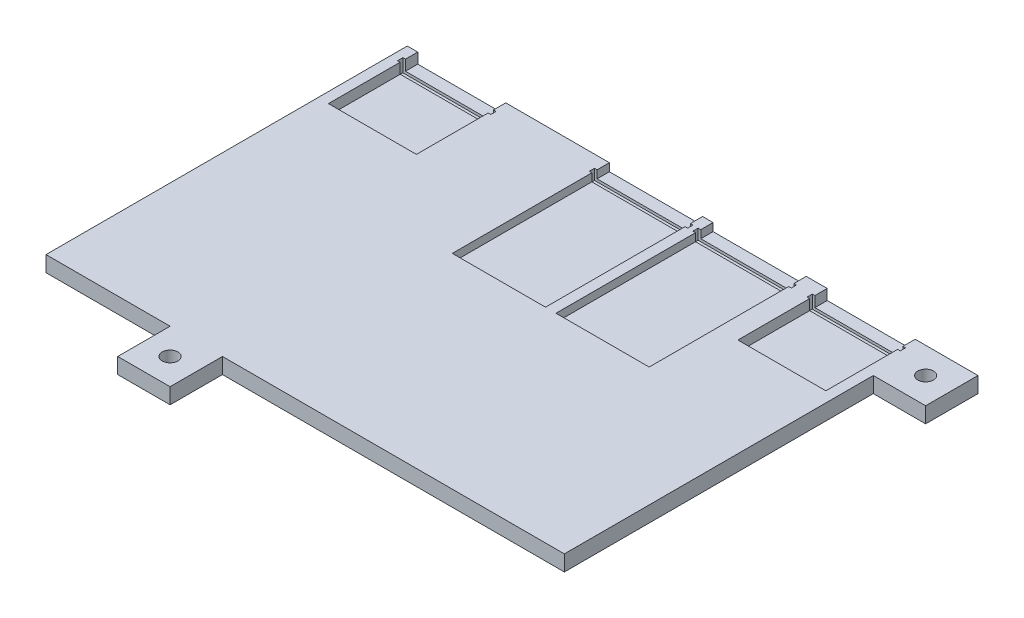
SolidWorks part; units mm, degrees
ref_plane "Front Plane" through (0, 0, 0) normal (0, 0, 1) x (1, 0, 0)
ref_plane "Top Plane" through (0, 0, 0) normal (0, 1, 0) x (1, 0, 0)
ref_plane "Right Plane" through (0, 0, 0) normal (1, 0, 0) x (0, 0, -1)
sketch "Sketch1" plane through (0, 0, 0) normal (0, 1, 0) x (1, 0, 0)
  line L1 (-49.5, 34.5) -> (49.5, 34.5)
  line L2 (-49.5, 34.5) -> (-49.5, -34.5)
  line L3 (-49.5, -34.5) -> (49.5, -34.5)
  line L4 (49.5, 34.5) -> (49.5, -34.5)
  line L5 (-49.5, 34.5) -> (49.5, -34.5) construction
  line L6 (-49.5, -34.5) -> (49.5, 34.5) construction
  point P4 (0, 0)
  point P5 (0, 0)
  dimension "D1" = 99
  dimension "D2" = 69
extrude "Boss-Extrude1" add sketch "Sketch1" along normal blind 3
sketch "Sketch2" plane through (0, 3, 0) normal (0, 1, 0) x (1, 0, 0)
  line L0 (-30.7, 32.1497) -> (-47.5, 32.1497) construction
  line L1 (-47.5, 32.1497) -> (-47.5, 34.5) construction
  line L2 (-47.5, 34.5) -> (-30.7, 34.5) construction
  line L3 (-30.7, 34.5) -> (-30.7, 32.1497) construction
  line L4 (-47.5, 31.1497) -> (-30.7, 31.1497) construction
  line L5 (-30.7, 31.1497) -> (-30.7, 17.4435) construction
  line L6 (-30.7, 17.4435) -> (-47.5, 17.4435) construction
  line L7 (-47.5, 17.4435) -> (-47.5, 31.1497) construction
  line L8 (6.9, 32.1497) -> (-10.9, 32.1497) construction
  line L9 (-10.9, 32.1497) -> (-10.9, 34.5) construction
  line L10 (-10.9, 34.5) -> (6.9, 34.5) construction
  line L11 (6.9, 34.5) -> (6.9, 32.1497) construction
  line L12 (-10.9, 31.1497) -> (6.9, 31.1497) construction
  line L13 (6.9, 31.1497) -> (6.9, 17.4435) construction
  line L14 (6.9, 17.4435) -> (-10.9, 17.4435) construction
  line L15 (-10.9, 17.4435) -> (-10.9, 31.1497) construction
  line L16 (8.9, 31.1497) -> (26.7, 31.1497) construction
  line L17 (26.7, 31.1497) -> (26.7, 17.4435) construction
  line L18 (26.7, 17.4435) -> (8.9, 17.4435) construction
  line L19 (8.9, 17.4435) -> (8.9, 31.1497) construction
  line L20 (26.7, 32.1497) -> (8.9, 32.1497) construction
  line L21 (8.9, 32.1497) -> (8.9, 34.5) construction
  line L22 (8.9, 34.5) -> (26.7, 34.5) construction
  line L23 (26.7, 34.5) -> (26.7, 32.1497) construction
  line L24 (47.5, 32.1497) -> (30.7, 32.1497) construction
  line L25 (30.7, 32.1497) -> (30.7, 34.5) construction
  line L26 (30.7, 34.5) -> (47.5, 34.5) construction
  line L27 (47.5, 34.5) -> (47.5, 32.1497) construction
  line L28 (30.7, 31.1497) -> (47.5, 31.1497) construction
  line L29 (47.5, 31.1497) -> (47.5, 17.4435) construction
  line L30 (47.5, 17.4435) -> (30.7, 17.4435) construction
  line L31 (30.7, 17.4435) -> (30.7, 31.1497) construction
  line L32 (-30.7, 32.1497) -> (-47.5, 32.1497)
  line L33 (-47.5, 32.1497) -> (-47.5, 34.5)
  line L34 (-47.5, 34.5) -> (-30.7, 34.5)
  line L35 (-30.7, 34.5) -> (-30.7, 32.1497)
  line L36 (-47.5, 31.1497) -> (-30.7, 31.1497)
  line L37 (-30.7, 31.1497) -> (-30.7, 17.4435)
  line L38 (-30.7, 17.4435) -> (-47.5, 17.4435)
  line L39 (-47.5, 17.4435) -> (-47.5, 31.1497)
  line L40 (6.9, 32.1497) -> (-10.9, 32.1497)
  line L41 (-10.9, 32.1497) -> (-10.9, 34.5)
  line L42 (-10.9, 34.5) -> (6.9, 34.5)
  line L43 (6.9, 34.5) -> (6.9, 32.1497)
  line L44 (-10.9, 31.1497) -> (6.9, 31.1497)
  line L45 (6.9, 31.1497) -> (6.9, 17.4435)
  line L46 (6.9, 17.4435) -> (-10.9, 17.4435)
  line L47 (-10.9, 17.4435) -> (-10.9, 31.1497)
  line L48 (8.9, 31.1497) -> (26.7, 31.1497)
  line L49 (26.7, 31.1497) -> (26.7, 17.4435)
  line L50 (26.7, 17.4435) -> (8.9, 17.4435)
  line L51 (8.9, 17.4435) -> (8.9, 31.1497)
  line L52 (26.7, 32.1497) -> (8.9, 32.1497)
  line L53 (8.9, 32.1497) -> (8.9, 34.5)
  line L54 (8.9, 34.5) -> (26.7, 34.5)
  line L55 (26.7, 34.5) -> (26.7, 32.1497)
  line L56 (47.5, 32.1497) -> (30.7, 32.1497)
  line L57 (30.7, 32.1497) -> (30.7, 34.5)
  line L58 (30.7, 34.5) -> (47.5, 34.5)
  line L59 (47.5, 34.5) -> (47.5, 32.1497)
  line L60 (30.7, 31.1497) -> (47.5, 31.1497)
  line L61 (47.5, 31.1497) -> (47.5, 17.4435)
  line L62 (47.5, 17.4435) -> (30.7, 17.4435)
  line L63 (30.7, 17.4435) -> (30.7, 31.1497)
sketch "Sketch4" plane through (0, 3, 0) normal (0, 1, 0) x (1, 0, 0)
  line L0 (47.5, 31.1497) -> (47.5, 17.4435) construction
  line L1 (47.5, 17.4435) -> (30.7, 17.4435) construction
  line L2 (30.7, 17.4435) -> (30.7, 31.1497) construction
  line L3 (-47.5, 17.4435) -> (-47.5, 31.1497) construction
  line L4 (-30.7, 31.1497) -> (-30.7, 17.4435) construction
  line L5 (-30.7, 17.4435) -> (-47.5, 17.4435) construction
  line L6 (47.5, 31.1497) -> (47.5, 17.4435)
  line L7 (47.5, 17.4435) -> (30.7, 17.4435)
  line L8 (30.7, 17.4435) -> (30.7, 31.1497)
  line L9 (-47.5, 17.4435) -> (-47.5, 31.1497)
  line L10 (-30.7, 31.1497) -> (-30.7, 17.4435)
  line L11 (-30.7, 17.4435) -> (-47.5, 17.4435)
  line L12 (-47.5, 31.1497) -> (-47.5, 34.5)
  line L13 (49.5, 34.5) -> (-49.5, 34.5) construction
  line L14 (-47.5, 34.5) -> (-30.7, 34.5)
  line L15 (-30.7, 34.5) -> (-30.7, 31.1497)
  line L16 (30.7, 31.1497) -> (30.7, 34.5)
  line L17 (30.7, 34.5) -> (47.5, 34.5)
  line L18 (47.5, 34.5) -> (47.5, 31.1497)
extrude "Cut-Extrude1" cut sketch "Sketch4" against normal blind 2
sketch "Sketch6" plane through (0, 1, 0) normal (0, 1, 0) x (1, 0, 0)
  line L1 (-47.5, 31.1497) -> (-48, 31.1497)
  line L2 (-47.5, 31.1497) -> (-47.5, 32.1497)
  line L3 (-47.5, 32.1497) -> (-48, 32.1497)
  line L4 (-48, 31.1497) -> (-48, 32.1497)
  line L5 (-47.5, 31.1497) -> (-48, 32.1497) construction
  line L6 (-47.5, 32.1497) -> (-48, 31.1497) construction
  line L7 (-30.7, 31.1497) -> (-30.2, 31.1497)
  line L8 (-30.7, 31.1497) -> (-30.7, 32.1497)
  line L9 (-30.7, 32.1497) -> (-30.2, 32.1497)
  line L10 (-30.2, 31.1497) -> (-30.2, 32.1497)
  line L11 (-30.7, 31.1497) -> (-30.2, 32.1497) construction
  line L12 (-30.7, 32.1497) -> (-30.2, 31.1497) construction
  line L13 (47.5, 31.1497) -> (48, 31.1497)
  line L14 (47.5, 31.1497) -> (47.5, 32.1497)
  line L15 (47.5, 32.1497) -> (48, 32.1497)
  line L16 (48, 31.1497) -> (48, 32.1497)
  line L17 (47.5, 31.1497) -> (48, 32.1497) construction
  line L18 (47.5, 32.1497) -> (48, 31.1497) construction
  line L19 (30.7, 31.1497) -> (30.2, 31.1497)
  line L20 (30.7, 31.1497) -> (30.7, 32.1497)
  line L21 (30.7, 32.1497) -> (30.2, 32.1497)
  line L22 (30.2, 31.1497) -> (30.2, 32.1497)
  line L23 (30.7, 31.1497) -> (30.2, 32.1497) construction
  line L24 (30.7, 32.1497) -> (30.2, 31.1497) construction
  point P4 (-47.75, 31.6497)
  point P10 (-30.45, 31.6497)
  point P16 (47.75, 31.6497)
  point P22 (30.45, 31.6497)
  dimension "D1" = 1
  dimension "D2" = 1
  dimension "D3" = 1
  dimension "D4" = 1
  dimension "D5" = 0.5
extrude "Cut-Extrude3" cut sketch "Sketch6" along normal blind 2
sketch "Sketch5" plane through (0, 1, 0) normal (0, 1, 0) x (1, 0, 0)
  line L0 (47.5, 32.1497) -> (30.7, 32.1497) construction
  line L1 (30.7, 31.1497) -> (47.5, 31.1497) construction
  line L2 (-30.7, 32.1497) -> (-47.5, 32.1497) construction
  line L3 (-47.5, 31.1497) -> (-30.7, 31.1497) construction
  line L4 (48, 32.1497) -> (30.2, 32.1497)
  line L5 (30.2, 31.1497) -> (48, 31.1497)
  line L6 (-30.2, 32.1497) -> (-48, 32.1497)
  line L7 (-48, 31.1497) -> (-30.2, 31.1497)
  line L8 (-48, 31.1497) -> (-48, 32.1497)
  line L9 (-30.2, 31.1497) -> (-30.2, 32.1497)
  line L10 (30.2, 31.1497) -> (30.2, 32.1497)
  line L11 (48, 31.1497) -> (48, 32.1497)
  line L12 (-30.2, 31.1497) -> (-30.2, 32.1497) construction
  line L13 (-48, 32.1497) -> (-48, 31.1497) construction
  line L16 (48, 31.1497) -> (48, 32.1497) construction
  line L17 (30.2, 32.1497) -> (30.2, 31.1497) construction
extrude "Cut-Extrude2" cut sketch "Sketch5" against normal blind 0.5
sketch "Sketch7" plane through (0, 3, 0) normal (0, 1, 0) x (1, 0, 0)
  line L0 (-10.9, 31.1497) -> (-10.9, 4.5)
  line L1 (-10.9, 34.5) -> (6.9, 34.5)
  line L2 (-10.9, 34.5) -> (-10.9, 32.1497)
  line L3 (-10.9, 4.5) -> (6.9, 4.5)
  line L4 (6.9, 34.5) -> (6.9, 32.1497)
  line L5 (-10.9, 34.5) -> (6.9, 4.5) construction
  line L6 (-10.9, 4.5) -> (6.9, 34.5) construction
  line L7 (8.9, 34.5) -> (26.7, 34.5)
  line L8 (8.9, 34.5) -> (8.9, 32.1497)
  line L9 (8.9, 4.5) -> (26.7, 4.5)
  line L10 (26.7, 34.5) -> (26.7, 32.1497)
  line L11 (8.9, 34.5) -> (26.7, 4.5) construction
  line L12 (8.9, 4.5) -> (26.7, 34.5) construction
  line L13 (-10.9, 31.1497) -> (-11.4, 31.1497)
  line L15 (-10.9, 32.1497) -> (-11.4, 32.1497)
  line L16 (-11.4, 31.1497) -> (-11.4, 32.1497)
  line L17 (-10.9, 31.1497) -> (-11.4, 32.1497) construction
  line L18 (-10.9, 32.1497) -> (-11.4, 31.1497) construction
  line L23 (6.9, 31.1497) -> (7.4, 31.1497)
  line L29 (6.9, 32.1497) -> (7.4, 32.1497)
  line L30 (7.4, 31.1497) -> (7.4, 32.1497)
  line L31 (6.9, 31.1497) -> (7.4, 32.1497) construction
  line L32 (26.7, 31.1497) -> (27.2, 31.1497)
  line L34 (26.7, 32.1497) -> (27.2, 32.1497)
  line L35 (27.2, 31.1497) -> (27.2, 32.1497)
  line L36 (26.7, 31.1497) -> (27.2, 32.1497) construction
  line L37 (26.7, 32.1497) -> (27.2, 31.1497) construction
  line L38 (6.9, 32.1497) -> (7.4, 31.1497) construction
  line L39 (8.9, 31.1497) -> (8.4, 31.1497)
  line L41 (8.9, 32.1497) -> (8.4, 32.1497)
  line L42 (8.4, 31.1497) -> (8.4, 32.1497)
  line L43 (8.9, 31.1497) -> (8.4, 32.1497) construction
  line L44 (8.9, 32.1497) -> (8.4, 31.1497) construction
  line L45 (6.9, 31.1497) -> (6.9, 4.5)
  line L46 (8.9, 31.1497) -> (8.9, 4.5)
  line L47 (26.7, 31.1497) -> (26.7, 4.5)
  point P4 (-2, 19.5)
  point P10 (17.8, 19.5)
  point P16 (-11.15, 31.6497)
  point P22 (7.15, 31.6497)
  point P28 (8.65, 31.6497)
  point P35 (26.95, 31.6497)
  dimension "D1" = 30
  dimension "D2" = 30
  dimension "D3" = 1
  dimension "D4" = 0.5
extrude "Cut-Extrude4" cut sketch "Sketch7" against normal blind 1.5
sketch "Sketch8" plane through (0, 1.5, 0) normal (0, 1, 0) x (1, 0, 0)
  line L1 (-11.4, 32.1497) -> (7.4, 32.1497)
  line L2 (-11.4, 32.1497) -> (-11.4, 31.1497)
  line L3 (-11.4, 31.1497) -> (7.4, 31.1497)
  line L4 (7.4, 32.1497) -> (7.4, 31.1497)
  line L5 (-11.4, 32.1497) -> (7.4, 31.1497) construction
  line L6 (-11.4, 31.1497) -> (7.4, 32.1497) construction
  line L7 (8.4, 32.1497) -> (27.2, 32.1497)
  line L8 (8.4, 32.1497) -> (8.4, 31.1497)
  line L9 (8.4, 31.1497) -> (27.2, 31.1497)
  line L10 (27.2, 32.1497) -> (27.2, 31.1497)
  line L11 (8.4, 32.1497) -> (27.2, 31.1497) construction
  line L12 (8.4, 31.1497) -> (27.2, 32.1497) construction
  point P4 (-2, 31.6497)
  point P11 (17.8, 31.6497)
extrude "Cut-Extrude5" cut sketch "Sketch8" against normal blind 0.5
sketch "Sketch9" plane through (0, 0, 0) normal (0, -1, 0) x (1, 0, 0)
  line L1 (-25.8, 34.5) -> (-15.8, 34.5)
  line L2 (-25.8, 34.5) -> (-25.8, 44.5)
  line L3 (-25.8, 44.5) -> (-15.8, 44.5)
  line L4 (-15.8, 34.5) -> (-15.8, 44.5)
  line L5 (-25.8, 34.5) -> (-15.8, 44.5) construction
  line L6 (-25.8, 44.5) -> (-15.8, 34.5) construction
  line L7 (-28.7, 35.0501) -> (-25.8, 35.0501) construction
  line L8 (-28.7, 41.1565) -> (-28.7, 34.5565) construction
  line L9 (-25.8, 35.0501) -> (-15.8, 35.0501) construction
  line L10 (-15.8, 35.0501) -> (-12.9, 35.0501) construction
  line L11 (-12.9, 34.5565) -> (-12.9, 41.1565) construction
  line L13 (49.5, -34.5) -> (59.5, -34.5)
  line L14 (49.5, -34.5) -> (49.5, -24.5)
  line L15 (49.5, -24.5) -> (59.5, -24.5)
  line L16 (59.5, -34.5) -> (59.5, -24.5)
  line L17 (49.5, -34.5) -> (59.5, -24.5) construction
  line L18 (49.5, -24.5) -> (59.5, -34.5) construction
  line L20 (-49.5, 34.5) -> (49.5, 34.5) construction
  point P4 (-20.8, 39.5)
  point P19 (54.5, -29.5)
  dimension "D1" = 10
  dimension "D2" = 10
  dimension "D3" = 10
  dimension "D4" = 10
extrude "Boss-Extrude2" add sketch "Sketch9" against normal up to surface (3 mm away) up to face at (3.6462, 3, -26.4724)
sketch "Sketch10" plane through (0, 3, 0) normal (0, 1, 0) x (1, 0, 0)
  line L0 (-20.8, -44.5) -> (-20.8, -35.6102) construction
  line L1 (-15.8, -44.5) -> (-25.8, -44.5) construction
  line L2 (-20.8, -35.6102) -> (-15.8, -39.5) construction
  line L3 (-15.8, -34.5) -> (-15.8, -44.5) construction
  line L4 (-15.8, -39.5) -> (-20.8, -39.5) construction
  line L5 (54.5, 24.5) -> (54.5, 31.9109) construction
  line L6 (59.5, 24.5) -> (49.5, 24.5) construction
  line L7 (54.5, 31.9109) -> (59.5, 29.5) construction
  line L8 (59.5, 34.5) -> (59.5, 24.5) construction
  line L9 (59.5, 29.5) -> (54.5, 29.5) construction
  circle A1 centre (-20.8, -39.5) radius 1.5
  circle A2 centre (54.5, 29.5) radius 1.5
  dimension "D1" = 3
  dimension "D2" = 3
extrude "Cut-Extrude6" cut sketch "Sketch10" against normal up to surface (3 mm away) up to face at (3.58, 0, 10.9)
